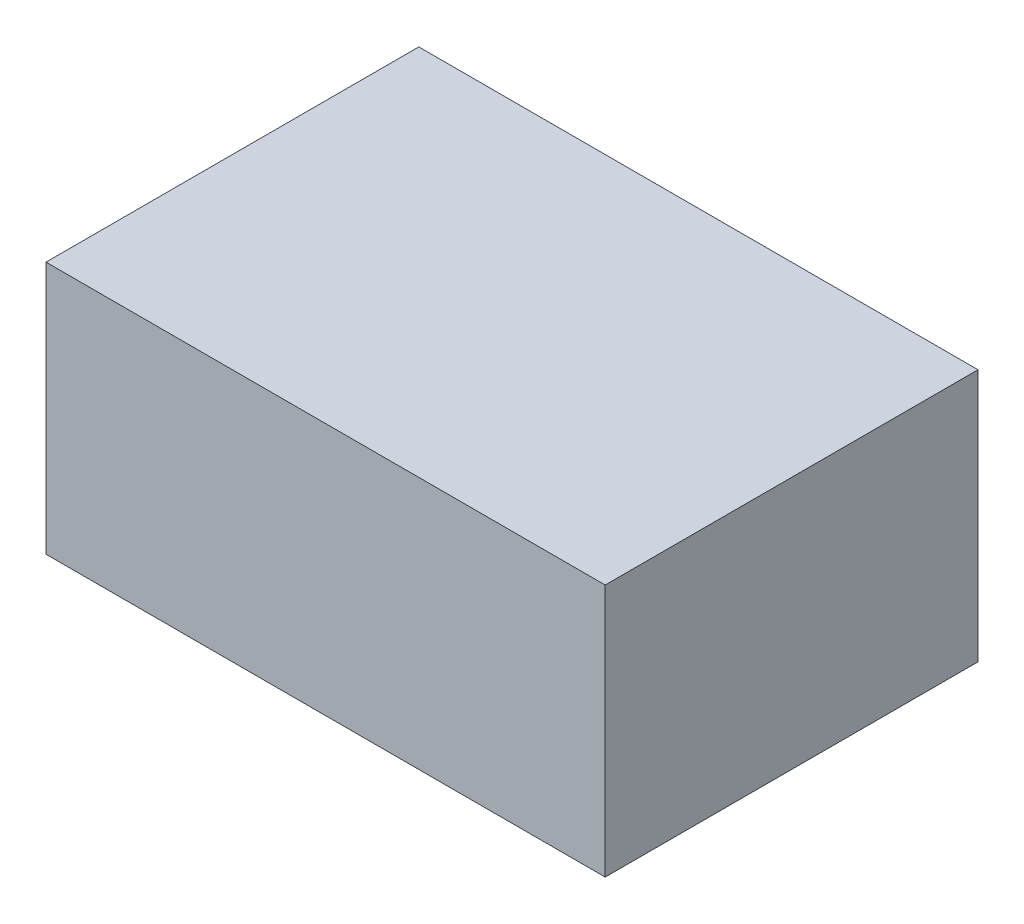
SolidWorks part; units mm, degrees
material "ПК/АБС"
ref_plane "Спереди" through (0, 0, 0) normal (0, 0, 1) x (1, 0, 0)
ref_plane "Сверху" through (0, 0, 0) normal (0, 1, 0) x (1, 0, 0)
ref_plane "Справа" through (0, 0, 0) normal (1, 0, 0) x (0, 0, -1)
sketch "Эскиз1" plane through (0, 0, 0) normal (0, 1, 0) x (1, 0, 0)
  line L1 (-2.1, 1.4) -> (2.1, 1.4)
  line L2 (-2.1, 1.4) -> (-2.1, -1.4)
  line L3 (-2.1, -1.4) -> (2.1, -1.4)
  line L4 (2.1, 1.4) -> (2.1, -1.4)
  line L5 (-2.1, 1.4) -> (2.1, -1.4) construction
  line L6 (-2.1, -1.4) -> (2.1, 1.4) construction
  point P0 (0, 0)
extrude "Бобышка-Вытянуть1" add sketch "Эскиз1" along normal blind 1.9
